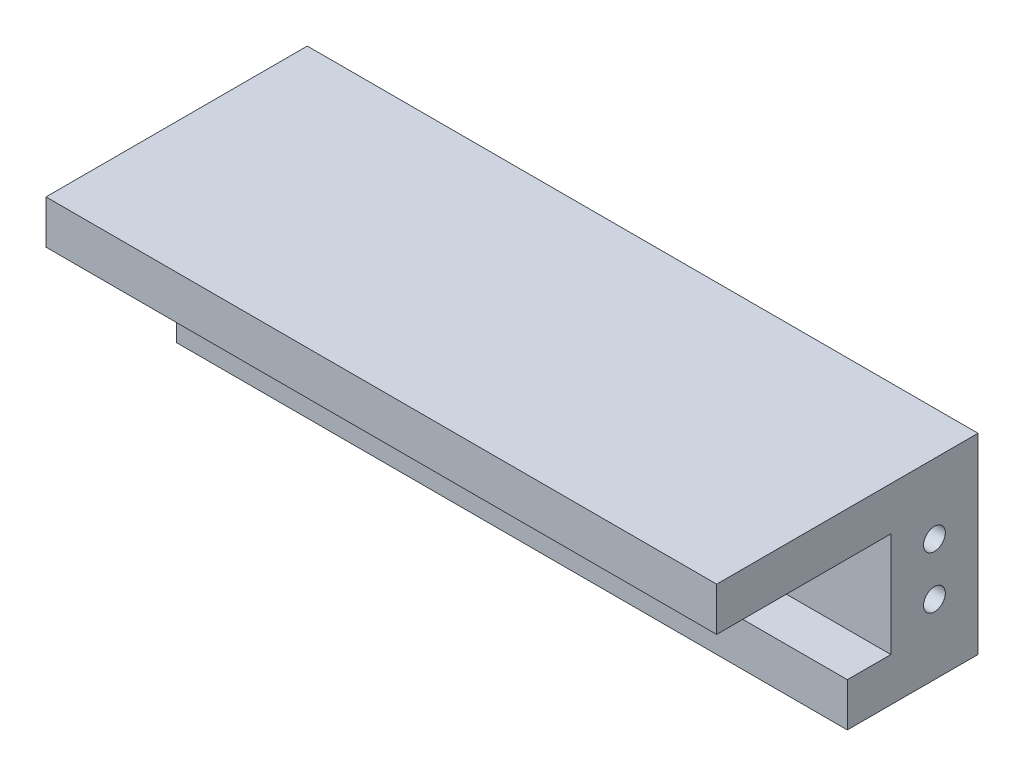
SolidWorks part; units mm, degrees
ref_plane "Front" through (0, 0, 0) normal (0, 0, 1) x (1, 0, 0)
ref_plane "Top" through (0, 0, 0) normal (0, 1, 0) x (1, 0, 0)
ref_plane "Right" through (0, 0, 0) normal (1, 0, 0) x (0, 0, -1)
sketch "Sketch1" plane through (0, 0, 0) normal (0, 0, 1) x (1, 0, 0)
  line L1 (0, 0) -> (77, 0)
  line L2 (0, 0) -> (0, 12)
  line L3 (0, 12) -> (77, 12)
  line L4 (77, 0) -> (77, 12)
  dimension "D1" = 77
  dimension "D2" = 12
extrude "Boss-Extrude1" add sketch "Sketch1" along normal blind 10
sketch "Sketch2" plane through (77, 0, 0) normal (1, 0, 0) x (0, 0, -1)
  line L0 (-5, 0) -> (-5, 12)
  line L1 (-10, 0) -> (0, 0) construction
  line L2 (-10, 12) -> (0, 12) construction
  line L3 (-5, 6) -> (-5, 12)
  line L4 (-5, 6) -> (-5, 0)
  circle A0 centre (-5, 3) radius 1.25
  circle A1 centre (-5, 9) radius 1.25
  dimension "D1" = 3
extrude "Cut-Extrude1" cut sketch "Sketch2" against normal blind 12 contours A0 | A1
ref_plane "Plane1" through (38.5, 0, 0) normal (-1, 0, 0) x (0, 0, 1)
sketch "Sketch3" plane through (0, 12, 0) normal (0, 1, 0) x (1, 0, 0)
  line L0 (77, 0) -> (0, 0)
  line L1 (77, 0) -> (77, -20)
  line L2 (0, 0) -> (0, -20)
  line L3 (77, -20) -> (0, -20)
  dimension "D1" = 20
extrude "Boss-Extrude2" add sketch "Sketch3" along normal blind 5
ref_plane "Plane2" through (0, 6, 0) normal (0, -1, 0) x (-1, 0, 0)
mirror "Mirror2" about plane through (0, 6, 0) normal (0, -1, 0) of "Boss-Extrude2"
sketch "Sketch4" plane through (0, 0, 0) normal (0, 0, -1) x (-1, 0, 0)
  line L0 (-77, 6) -> (0, 6)
  line L1 (-77, -5) -> (-77, 17) construction
  line L2 (0, 17) -> (0, -5) construction
  line L3 (-53.5, 12) -> (-53.5, 0)
  line L4 (-53.5, 12) -> (-23.5, 12)
  line L5 (-53.5, 0) -> (-23.5, 0)
  line L6 (-23.5, 12) -> (-23.5, 0)
  line L7 (-53.5, 12) -> (-23.5, 0) construction
  line L8 (-53.5, 0) -> (-23.5, 12) construction
  point P7 (-38.5, 6)
  dimension "D1" = 12
  dimension "D2" = 30
  dimension "D3" = 38.5
extrude "Cut-Extrude2" cut sketch "Sketch4" against normal blind 10 contours L6 L4 L3 L0 | L6 L0 L3 L5
sketch "Sketch5" plane through (0, 0, 20) normal (0, 0, 1) x (1, 0, 0)
  line L0 (0, -2.5) -> (77, -2.5)
  line L1 (0, -5) -> (0, 0) construction
  line L2 (77, -5) -> (77, 0) construction
  line L3 (-0.5, -5) -> (-0.5, 0)
  line L4 (-0.5, -5) -> (77.5, -5)
  line L5 (-0.5, 0) -> (77.5, 0)
  line L6 (77.5, -5) -> (77.5, 0)
  line L7 (-0.5, -5) -> (77.5, 0) construction
  line L8 (-0.5, 0) -> (77.5, -5) construction
  line L9 (0, 12) -> (0, 0) construction
  point P7 (38.5, -2.5)
  line M2 (77, 0) -> (0, 0)
  line M4 (0, -5) -> (77, -5)
  dimension "D1" = 78
  dimension "D2" = 38.5
extrude "Cut-Extrude3" cut sketch "Sketch5" against normal blind 5 contours L0 L6 L3 M2 | L6 L0 L3 M4
sketch "Sketch6" plane through (0, 0, 0) normal (-1, 0, 0) x (0, 0, 1)
  line L0 (10, 6) -> (0, 6)
  line L1 (10, 12) -> (10, 0) construction
  line L2 (0, 17) -> (0, -5) construction
  circle A0 centre (5, 6) radius 1.25
extrude "Cut-Extrude4" cut sketch "Sketch6" against normal blind 12 contours L0 A0 | L0 A0
sketch "Sketch8" plane through (0, 0, 20) normal (0, 0, 1) x (1, 0, 0)
  line L1 (77, 12) -> (0, 12)
  line L2 (77, 12) -> (77, 17)
  line L3 (77, 17) -> (0, 17)
  line L4 (0, 12) -> (0, 17)
extrude "Boss-Extrude3" add sketch "Sketch8" along normal blind 10
